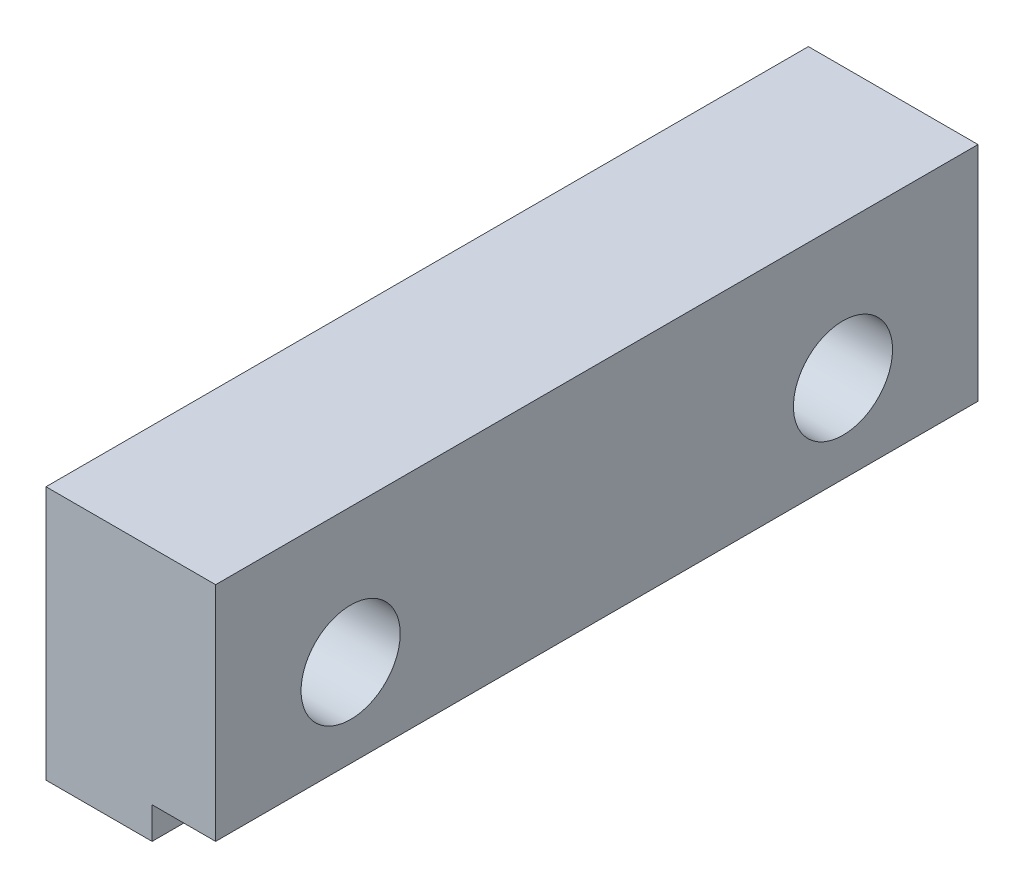
SolidWorks part; units mm, degrees
ref_plane "Front Plane" through (0, 0, 0) normal (0, 0, 1) x (1, 0, 0)
ref_plane "Top Plane" through (0, 0, 0) normal (0, 1, 0) x (1, 0, 0)
ref_plane "Right Plane" through (0, 0, 0) normal (1, 0, 0) x (0, 0, -1)
sketch "Sketch1" plane through (0, 0, 0) normal (0, 0, 1) x (1, 0, 0)
  line L1 (16.9545, -25.4) -> (-16.9545, -25.4)
  line L2 (16.9545, -25.4) -> (16.9545, 25.4)
  line L3 (16.9545, 25.4) -> (-16.9545, 25.4)
  line L4 (-16.9545, -25.4) -> (-16.9545, 25.4)
  line L5 (16.9545, -25.4) -> (-16.9545, 25.4) construction
  line L6 (16.9545, 25.4) -> (-16.9545, -25.4) construction
  point P0 (0, 0)
  dimension "D1" = 33.909
  dimension "D2" = 50.8
extrude "Boss-Extrude1" add sketch "Sketch1" along normal mid plane 152.4
sketch "Sketch2" plane through (16.9545, 0, 0) normal (1, 0, 0) x (0, 0, -1)
  line L0 (-76.2, -25.4) -> (76.2, -25.4) construction
  circle A0 centre (-49.2125, -1.524) radius 6.731
  circle A1 centre (49.2125, -1.524) radius 6.731
  dimension "D4" = 13.462
  dimension "D1" = 98.425
  dimension "D2" = 49.2125
  dimension "D3" = 23.876
extrude "Cut-Extrude1" cut sketch "Sketch2" against normal up to next
sketch "Sketch3" plane through (16.9545, 0, 0) normal (1, 0, 0) x (0, 0, -1)
  circle A0 centre (-49.2125, -1.524) radius 9.906
  circle A1 centre (49.2125, -1.524) radius 9.906
  dimension "D1" = 19.812
extrude "Cut-Extrude2" cut sketch "Sketch3" against normal offset from surface (28.956 mm away) 4.953 up to face at (-16.9545, -1.524, 42.4815)
sketch "Sketch4" plane through (0, 0, 76.2) normal (0, 0, 1) x (1, 0, 0)
  line L7 (16.9545, -25.4) -> (12.46, -25.4)
  line L8 (16.9545, -25.4) -> (16.9545, -19.05)
  line L9 (16.9545, -19.05) -> (12.46, -19.05)
  line L10 (12.46, -25.4) -> (12.46, -19.05)
  dimension "D1" = 4.4945
  dimension "D2" = 6.35
extrude "Cut-Extrude4" cut sketch "Sketch4" against normal through all
sketch "Sketch5" plane through (16.9545, 0, 0) normal (1, 0, 0) x (0, 0, -1)
  line L4 (-76.2, -19.05) -> (-76.2, -25.4)
  line L5 (-76.2, -25.4) -> (76.2, -25.4)
  line L6 (76.2, -25.4) -> (76.2, -19.05)
  line L7 (76.2, -19.05) -> (-76.2, -19.05)
  line L8 (-76.2, -19.05) -> (-76.2, -25.4)
  line L9 (-76.2, -25.4) -> (76.2, -25.4)
  line L10 (76.2, -25.4) -> (76.2, -19.05)
  line L11 (76.2, -19.05) -> (-76.2, -19.05)
  dimension "D1" = 0
extrude "Cut-Extrude5" cut sketch "Sketch5" against normal blind 12.7
